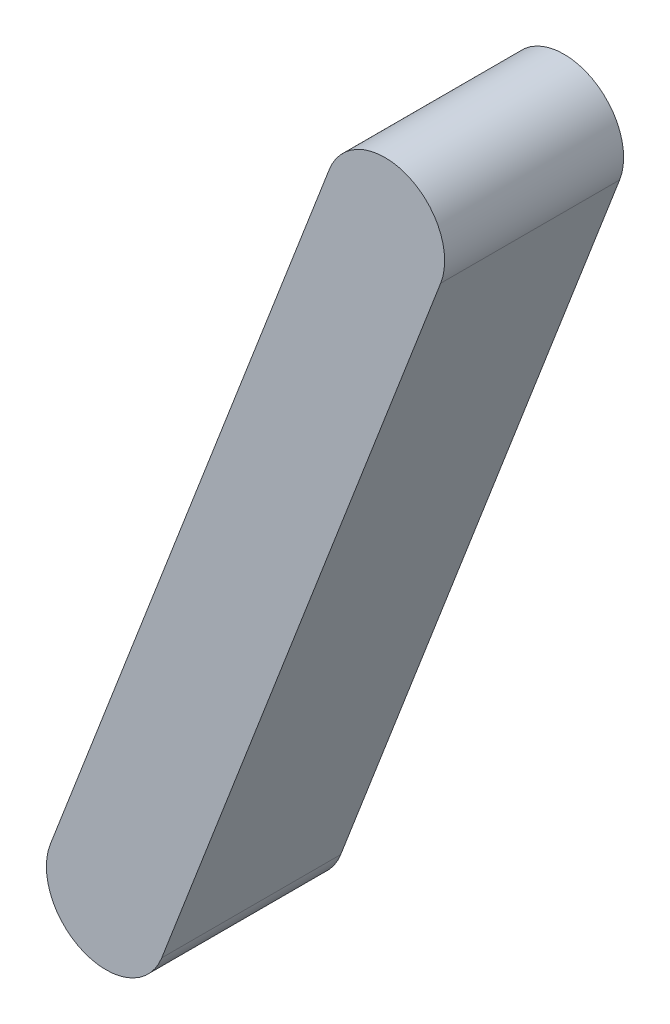
SolidWorks part; units mm, degrees
ref_plane "前视基准面" through (0, 0, 0) normal (0, 0, 1) x (1, 0, 0)
ref_plane "上视基准面" through (0, 0, 0) normal (0, 1, 0) x (1, 0, 0)
ref_plane "右视基准面" through (0, 0, 0) normal (1, 0, 0) x (0, 0, -1)
sketch "草图1" plane through (0, 0, 0) normal (0, 0, 1) x (1, 0, 0)
  line L0 (-17.2604, -48.0176) -> (29.4923, 73.2844) construction
  line L1 (-26.5913, -44.4213) -> (20.1613, 76.8808)
  line L2 (-7.9295, -51.614) -> (38.8232, 69.688)
  arc A0 (-26.5913, -44.4213) -> (-7.9295, -51.614) centre (-17.2604, -48.0176) ccw
  arc A1 (38.8232, 69.688) -> (20.1613, 76.8808) centre (29.4923, 73.2844) ccw
  point P0 (6.1159, 12.6334)
  dimension "D1" = 130
  dimension "D2" = 20
extrude "凸台-拉伸1" add sketch "草图1" along normal mid plane 30
